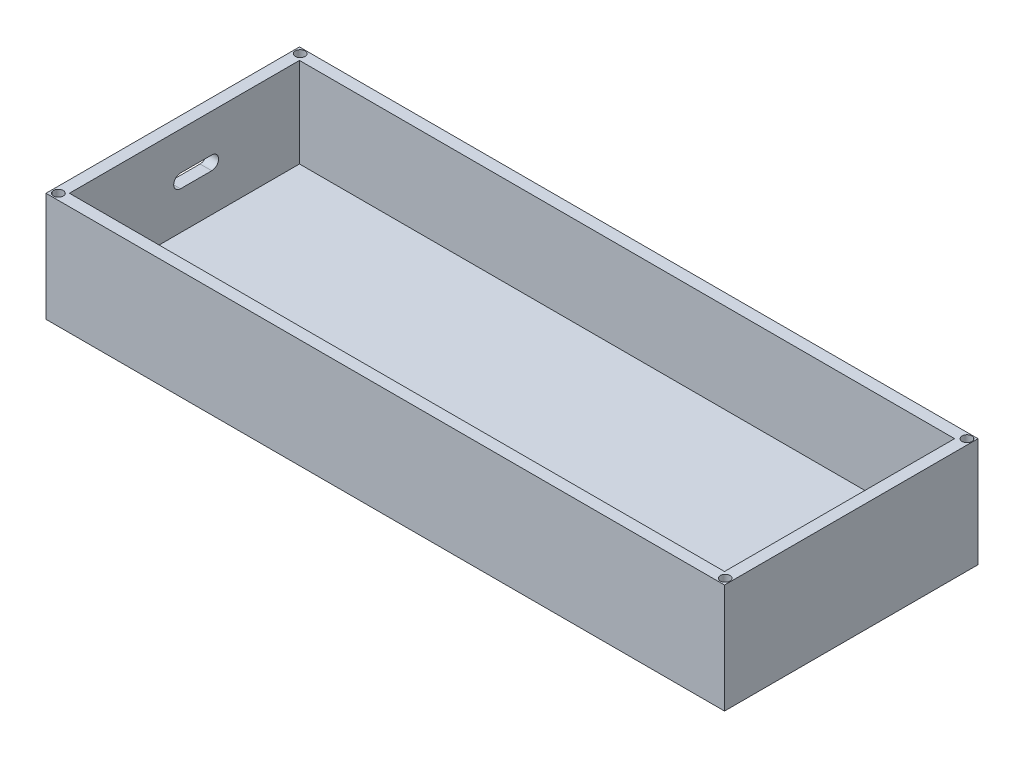
SolidWorks part; units mm, degrees
ref_plane "Front Plane" through (0, 0, 0) normal (0, 0, 1) x (1, 0, 0)
ref_plane "Top Plane" through (0, 0, 0) normal (0, 1, 0) x (1, 0, 0)
ref_plane "Right Plane" through (0, 0, 0) normal (1, 0, 0) x (0, 0, -1)
sketch "Sketch1" plane through (0, 0, 0) normal (0, 1, 0) x (1, 0, 0)
  line L1 (-43.5146, 31.0042) -> (130.4854, 31.0042)
  line L2 (-43.5146, 31.0042) -> (-43.5146, -33.9958)
  line L3 (-43.5146, -33.9958) -> (130.4854, -33.9958)
  line L4 (130.4854, 31.0042) -> (130.4854, -33.9958)
  point P4 (0, 0)
  dimension "D1" = 65
  dimension "D2" = 174
extrude "Boss-Extrude1" add sketch "Sketch1" along normal blind 5
sketch "Sketch2" plane through (0, 5, 0) normal (0, 1, 0) x (1, 0, 0)
  line L0 (-40.5146, -30.9958) -> (-40.5146, 28.0042)
  line L1 (-43.5146, -33.9958) -> (130.4854, -33.9958)
  line L2 (-43.5146, -33.9958) -> (-43.5146, 31.0042)
  line L3 (-43.5146, 31.0042) -> (130.4854, 31.0042)
  line L4 (130.4854, -33.9958) -> (130.4854, 31.0042)
  line L5 (-40.5146, 28.0042) -> (127.4854, 28.0042)
  line L6 (127.4854, -30.9958) -> (127.4854, 28.0042)
  line L7 (-40.5146, -30.9958) -> (127.4854, -30.9958)
  dimension "D1" = 3
extrude "Boss-Extrude2" add sketch "Sketch2" along normal blind 23
sketch "Sketch3" plane through (-43.5146, 0, 0) normal (-1, 0, 0) x (0, 0, 1)
  line L0 (-5.5042, 16.5) -> (2.4958, 16.5) construction
  line L1 (-5.5042, 18.25) -> (2.4958, 18.25)
  line L2 (-5.5042, 14.75) -> (2.4958, 14.75)
  line L3 (-31.0042, 28) -> (-31.0042, 0) construction
  line L4 (-31.0042, 0) -> (33.9958, 0) construction
  arc A0 (-5.5042, 18.25) -> (-5.5042, 14.75) centre (-5.5042, 16.5) ccw
  arc A1 (2.4958, 14.75) -> (2.4958, 18.25) centre (2.4958, 16.5) ccw
  point P2 (-1.5042, 16.5)
  dimension "D1" = 8
  dimension "D2" = 3.5
  dimension "D3" = 29.5
  dimension "D4" = 16.5
extrude "Cut-Extrude1" cut sketch "Sketch3" against normal blind 23
sketch "Sketch4" plane through (0, 28, 0) normal (0, 1, 0) x (1, 0, 0)
  line L0 (-43.5146, -33.9958) -> (-40.5146, -30.9958) construction
  circle A0 centre (-41.9289, -32.41) radius 1.25
  dimension "D1" = 2.5
  dimension "D2" = 2
extrude "Cut-Extrude2" cut sketch "Sketch4" against normal blind 4
pattern_linear "LPattern1" count 2 spacing 62 along (0, 0, -1) count 2 spacing 171 along (1, 0, 0) of "Cut-Extrude2"
